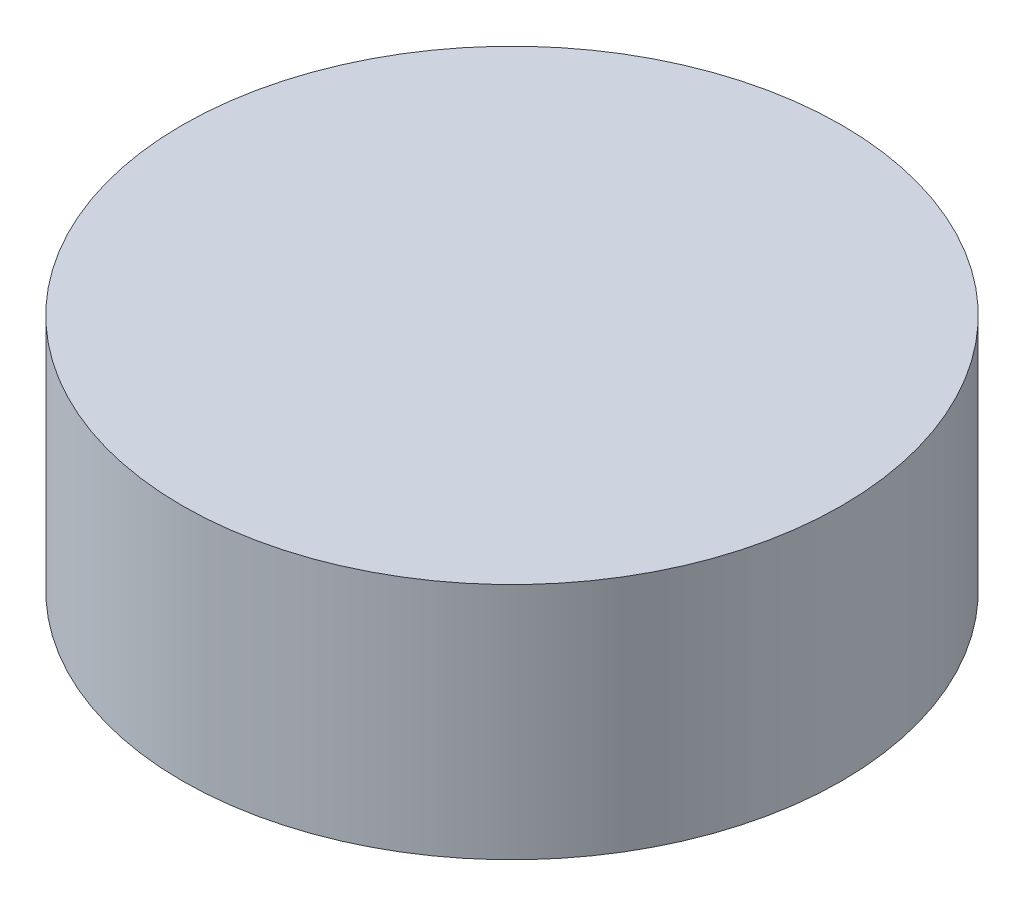
SolidWorks part; units mm, degrees
ref_plane "Front Plane" through (0, 0, 0) normal (0, 0, 1) x (1, 0, 0)
ref_plane "Top Plane" through (0, 0, 0) normal (0, 1, 0) x (1, 0, 0)
ref_plane "Right Plane" through (0, 0, 0) normal (1, 0, 0) x (0, 0, -1)
sketch "Sketch2" plane through (0, 14, 0) normal (0, 1, 0) x (1, 0, 0)
  line L0 (0, 0) -> (-0.498, 0)
  circle A2 centre (-0.498, 0) radius 12.45
  dimension "D1" = 24.9
extrude "Boss-Extrude2" add sketch "Sketch2" along normal blind 2 and the other way blind 7 contours A2
sketch "Sketch3" plane through (0, 7, 0) normal (0, -1, 0) x (1, 0, 0)
  line L0 (0, 0) -> (-0.5, 0) construction
  circle A0 centre (-0.5, 0) radius 10
  circle A1 centre (9.5, 0) radius 1.475
  circle A2 centre (4.5, -8.6603) radius 1.475
  circle A3 centre (-5.5, -8.6603) radius 1.475
  circle A4 centre (-10.5, 0) radius 1.475
  circle A5 centre (-5.5, 8.6603) radius 1.475
  circle A6 centre (4.5, 8.6603) radius 1.475
  dimension "D1" = 2.95
  dimension "D2" = 6
extrude "Cut-Extrude1" cut sketch "Sketch3" against normal blind 6.05 contours A1 | A6 | A5 | A4 | A3 | A2
sketch "Sketch4" plane through (0, 7, 0) normal (0, -1, 0) x (1, 0, 0)
  line L0 (0, 0) -> (-0.5, 0)
  circle A0 centre (-0.5, 0) radius 7
extrude "Cut-Extrude2" cut sketch "Sketch4" against normal blind 4.05 contours A0
